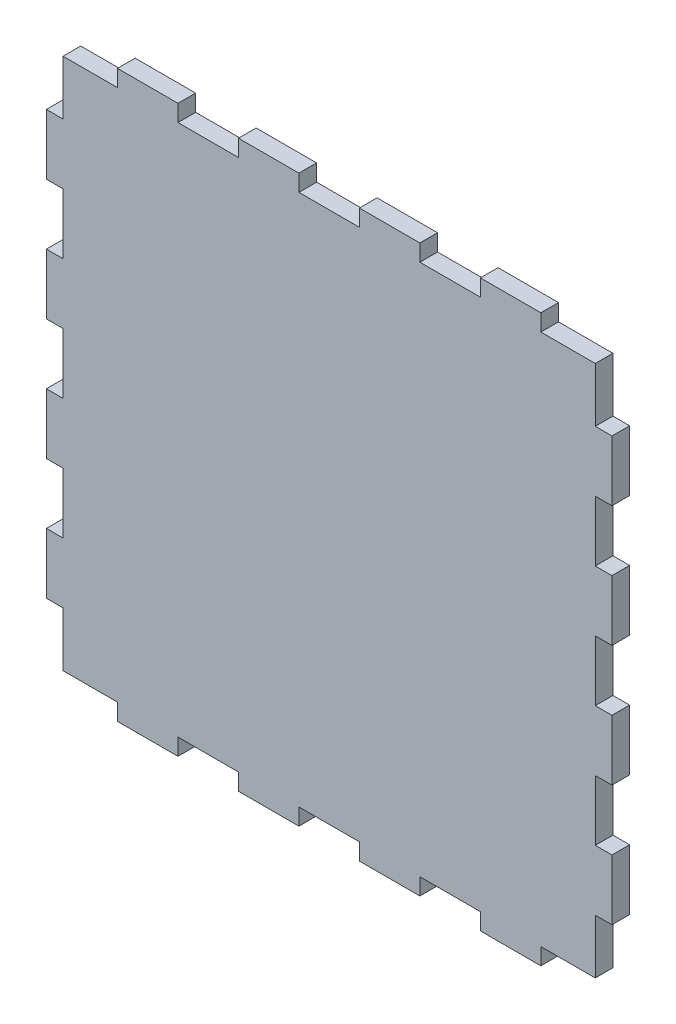
SolidWorks part; units mm, degrees
ref_plane "Front Plane" through (0, 0, 0) normal (0, 0, 1) x (1, 0, 0)
ref_plane "Top Plane" through (0, 0, 0) normal (0, 1, 0) x (1, 0, 0)
ref_plane "Right Plane" through (0, 0, 0) normal (1, 0, 0) x (0, 0, -1)
sketch "Sketch3" plane through (0, 0, 0) normal (0, 0, 1) x (1, 0, 0)
  line L68 (0, 177.6539) -> (0, 155.9242)
  line L69 (0, 155.9242) -> (5.9944, 155.9242)
  line L70 (5.9944, 155.9242) -> (5.9944, 134.1945)
  line L71 (5.9944, 134.1945) -> (0, 134.1945)
  line L72 (0, 134.1945) -> (0, 112.4648)
  line L73 (0, 112.4648) -> (5.9944, 112.4648)
  line L74 (5.9944, 112.4648) -> (5.9944, 90.7352)
  line L75 (5.9944, 90.7352) -> (0, 90.7352)
  line L76 (0, 90.7352) -> (0, 69.0054)
  line L77 (0, 69.0054) -> (5.9944, 69.0054)
  line L78 (5.9944, 69.0054) -> (5.9944, 47.2757)
  line L79 (5.9944, 47.2757) -> (0, 47.2757)
  line L80 (0, 47.2757) -> (0, 25.5461)
  line L81 (0, 25.5461) -> (5.9944, 25.5461)
  line L82 (5.9944, 25.5461) -> (5.9944, 5.9944)
  line L83 (5.9944, 5.9944) -> (25.5461, 5.9944)
  line L84 (25.5461, 5.9944) -> (25.5461, 0)
  line L85 (25.5461, 0) -> (47.2757, 0)
  line L86 (47.2757, 0) -> (47.2757, 5.9944)
  line L87 (47.2757, 5.9944) -> (69.0054, 5.9944)
  line L88 (69.0054, 5.9944) -> (69.0054, 0)
  line L89 (69.0054, 0) -> (90.7352, 0)
  line L90 (90.7352, 0) -> (90.7352, 5.9944)
  line L91 (90.7352, 5.9944) -> (112.4648, 5.9944)
  line L92 (112.4648, 5.9944) -> (112.4648, 0)
  line L93 (112.4648, 0) -> (134.1945, 0)
  line L94 (134.1945, 0) -> (134.1945, 5.9944)
  line L95 (134.1945, 5.9944) -> (155.9242, 5.9944)
  line L96 (155.9242, 5.9944) -> (155.9242, 0)
  line L97 (155.9242, 0) -> (177.6539, 0)
  line L98 (177.6539, 0) -> (177.6539, 5.9944)
  line L99 (177.6539, 5.9944) -> (197.2056, 5.9944)
  line L100 (197.2056, 5.9944) -> (197.2056, 25.5461)
  line L101 (197.2056, 25.5461) -> (203.2, 25.5461)
  line L102 (203.2, 25.5461) -> (203.2, 47.2757)
  line L103 (203.2, 47.2757) -> (197.2056, 47.2757)
  line L104 (197.2056, 47.2757) -> (197.2056, 69.0054)
  line L105 (197.2056, 69.0054) -> (203.2, 69.0054)
  line L106 (203.2, 69.0054) -> (203.2, 90.7352)
  line L107 (203.2, 90.7352) -> (197.2056, 90.7352)
  line L108 (197.2056, 90.7352) -> (197.2056, 112.4648)
  line L109 (197.2056, 112.4648) -> (203.2, 112.4648)
  line L110 (203.2, 112.4648) -> (203.2, 134.1945)
  line L111 (203.2, 134.1945) -> (197.2056, 134.1945)
  line L112 (197.2056, 134.1945) -> (197.2056, 155.9242)
  line L113 (197.2056, 155.9242) -> (203.2, 155.9242)
  line L114 (203.2, 155.9242) -> (203.2, 177.6539)
  line L115 (203.2, 177.6539) -> (197.2056, 177.6539)
  line L116 (197.2056, 177.6539) -> (197.2056, 197.2056)
  line L117 (197.2056, 197.2056) -> (177.6539, 197.2056)
  line L118 (177.6539, 197.2056) -> (177.6539, 203.2)
  line L119 (177.6539, 203.2) -> (155.9242, 203.2)
  line L120 (155.9242, 203.2) -> (155.9242, 197.2056)
  line L121 (155.9242, 197.2056) -> (134.1945, 197.2056)
  line L122 (134.1945, 197.2056) -> (134.1945, 203.2)
  line L123 (134.1945, 203.2) -> (112.4648, 203.2)
  line L124 (112.4648, 203.2) -> (112.4648, 197.2056)
  line L125 (112.4648, 197.2056) -> (90.7352, 197.2056)
  line L126 (90.7352, 197.2056) -> (90.7352, 203.2)
  line L127 (90.7352, 203.2) -> (69.0054, 203.2)
  line L128 (69.0054, 203.2) -> (69.0054, 197.2056)
  line L129 (69.0054, 197.2056) -> (47.2757, 197.2056)
  line L130 (47.2757, 197.2056) -> (47.2757, 203.2)
  line L131 (47.2757, 203.2) -> (25.5461, 203.2)
  line L132 (25.5461, 203.2) -> (25.5461, 197.2056)
  line L133 (25.5461, 197.2056) -> (5.9944, 197.2056)
  line L134 (5.9944, 197.2056) -> (5.9944, 177.6539)
  line L135 (5.9944, 177.6539) -> (0, 177.6539)
extrude "Boss-Extrude1" add sketch "Sketch3" along normal blind 6.35
